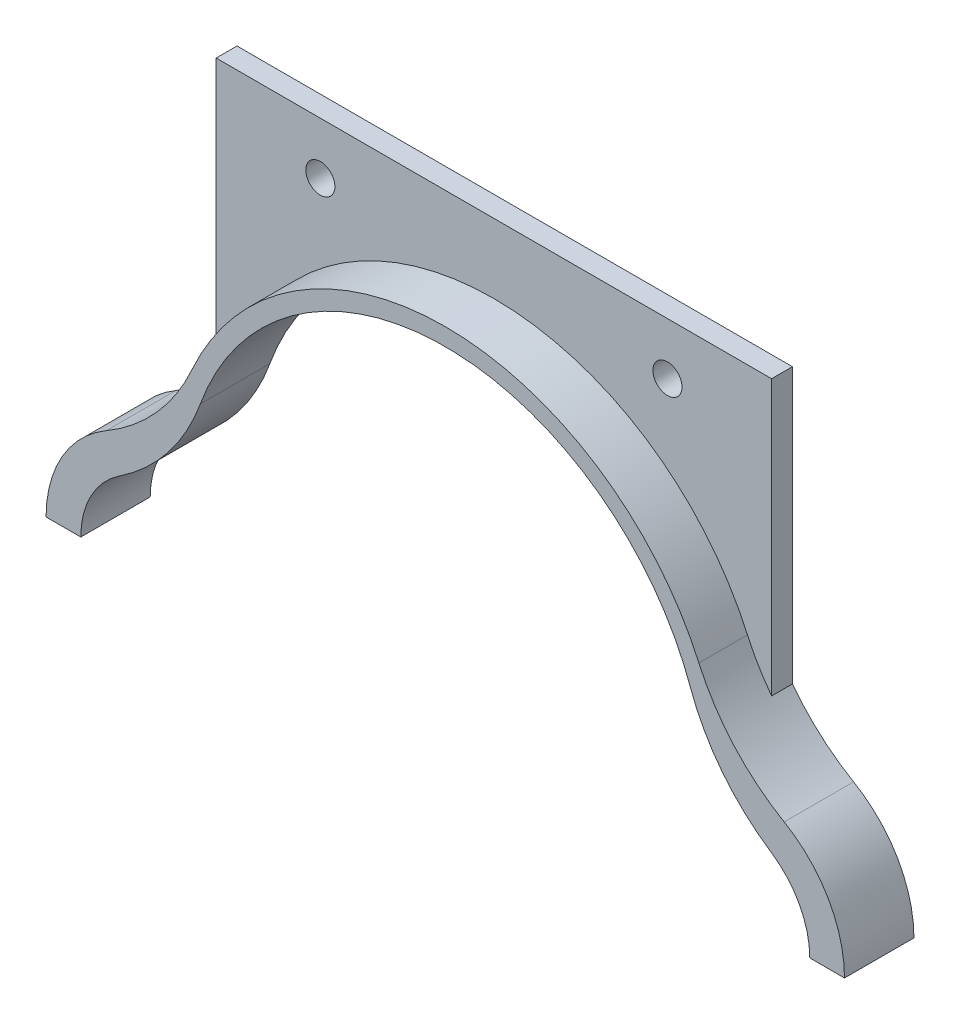
SolidWorks part; units mm, degrees
material "ABS"
ref_plane "前基準面" through (0, 0, 0) normal (0, 0, 1) x (1, 0, 0)
ref_plane "上基準面" through (0, 0, 0) normal (0, 1, 0) x (1, 0, 0)
ref_plane "右基準面" through (0, 0, 0) normal (1, 0, 0) x (0, 0, -1)
sketch "草圖1" plane through (0, 0, 0) normal (0, 0, 1) x (1, 0, 0)
  line L0 (-40, 0) -> (-37.5, 0)
  line L1 (37.5, 0) -> (40, 0)
  arc A0 (-40, 0) -> (40, 0) centre (0, 0) cw
  arc A1 (-37.5, 0) -> (37.5, 0) centre (0, 0) cw
  point P7 (38.75, 0)
  point P8 (-38.75, 0)
  dimension "D2" = 37.5
  dimension "D3" = 40
  dimension "D1" = 2.5
extrude "填料-伸長1" add sketch "草圖1" along normal blind 10
sketch "草圖2" plane through (0, 0, 0) normal (0, 0, -1) x (-1, 0, 0)
  line L0 (-40, 0) -> (-40, 50)
  line L1 (-40, 50) -> (40, 50)
  line L2 (40, 50) -> (40, 0)
  line L3 (40, 0) -> (37.5, 0) construction
  line L4 (-37.5, 0) -> (-40, 0) construction
  arc A0 (-40, 0) -> (40, 0) centre (0, 0) cw
  arc A1 (40, 0) -> (-40, 0) centre (0, 0) ccw construction
  point P15 (-38.75, 0)
  dimension "D1" = 50
extrude "填料-伸長2" add sketch "草圖2" against normal blind 3
sketch "草圖3" plane through (0, 0, 3) normal (0, 0, 1) x (1, 0, 0)
  line L0 (0, 0) -> (0, 50) construction
  line L1 (-40, 50) -> (40, 50) construction
  circle A0 centre (-25, 42.5) radius 2.1
  circle A1 centre (25, 42.5) radius 2.1
  dimension "D1" = 4.2
  dimension "D2" = 25
  dimension "D3" = 42.5
extrude "除料-伸長1" cut sketch "草圖3" against normal through all
sketch "草圖4" plane through (0, 0, 0) normal (0, 0, -1) x (-1, 0, 0)
  line L0 (0, 0) -> (0, 37.5) construction
  line L2 (57.5, -12.5) -> (52.5, -12.5)
  line L4 (40, 0) -> (40, 50) construction
  arc A0 (40, 0) -> (52.5, -12.5) centre (40, -12.5) cw
  arc A1 (40, 0) -> (-40, 0) centre (0, 0) ccw construction
  arc A2 (37.5, 0) -> (-37.5, 0) centre (0, 0) ccw construction
  arc A3 (39.6866, 4.9972) -> (57.5, -12.5) centre (40, -12.5) cw
  arc A4 (39.6866, 4.9972) -> (40, 0) centre (0, 0) cw
  line M9 (40, 0) -> (40, 50)
  dimension "D1" = 12.5
  dimension "D3" = 17.5
  dimension "D2" = 5
  dimension "D4" = 40
extrude "填料-伸長5" add sketch "草圖4" against normal up to surface (10 mm away) contours A3 A0 L2 M9 | A3 A4 M9
mirror "鏡射1" about plane through (0, 0, 0) normal (1, 0, 0) of "填料-伸長5"
fillet "圓角1" radius 30 2 edges at (37.5, 0, 5) (-37.5, 0, 5)
fillet "圓角2" radius 30 2 edges at (-39.6866, 4.9972, 6.5) (39.6866, 4.9972, 6.5)
